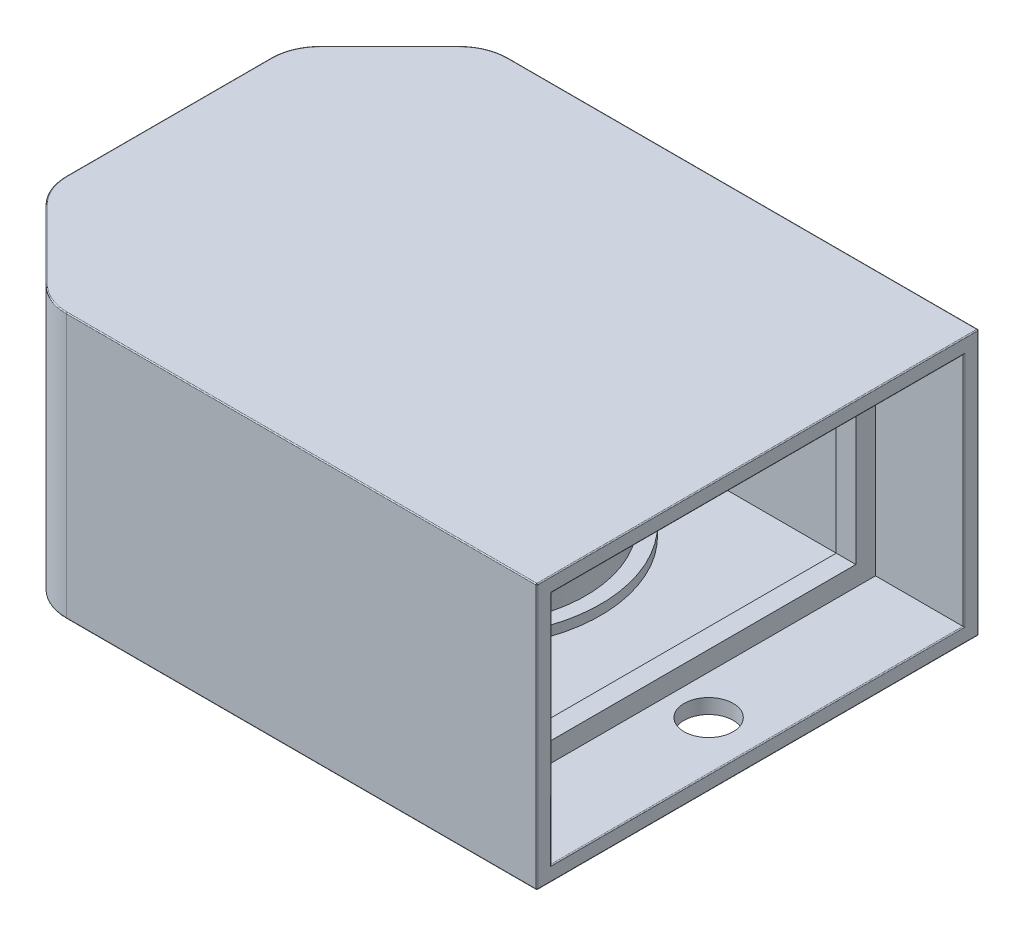
SolidWorks part; units mm, degrees
ref_plane "前视基准面" through (0, 0, 0) normal (0, 0, 1) x (1, 0, 0)
ref_plane "上视基准面" through (0, 0, 0) normal (0, 1, 0) x (1, 0, 0)
ref_plane "右视基准面" through (0, 0, 0) normal (1, 0, 0) x (0, 0, -1)
sketch "草图1" plane through (0, 0, 0) normal (0, 1, 0) x (1, 0, 0)
  line L1 (-30, -22.5) -> (30, -22.5)
  line L2 (-30, -22.5) -> (-30, 22.5)
  line L3 (-30, 22.5) -> (30, 22.5)
  line L4 (30, -22.5) -> (30, 22.5)
  line L5 (-30, -22.5) -> (30, 22.5) construction
  line L6 (-30, 22.5) -> (30, -22.5) construction
  point P0 (0, 0)
  dimension "D1" = 45
  dimension "D2" = 60
extrude "凸台-拉伸1" add sketch "草图1" along normal mid plane 27
chamfer "倒角1" distance 10 angle 45 2 edges at (-30, 0, -22.5) (-30, 0, 22.5)
fillet "圆角1" radius 5 4 edges at (-20, 0, -22.5) (-30, 0, -12.5) (-30, 0, 12.5) (-20, 0, 22.5)
shell "抽壳1" thickness 1.5
fillet "圆角2" radius 0.1 26 edges at (30, 0, -21) (30, 12, 0) (30, 0, 21) (30, -12, 0) (30, 0, 22.5) (30, 0, -22.5) (-29.6194, -13.5, -12.3423) (-30, -13.5, 0) (-29.6194, -13.5, 12.3423) (-25, -13.5, 17.5) (-19.8423, -13.5, 22.1194) (6.0355, -13.5, 22.5) (30, -13.5, 0) (6.0355, -13.5, -22.5) (-19.8423, -13.5, -22.1194) (-25, -13.5, -17.5) (30, 13.5, 0) (6.0355, 13.5, 22.5) (-19.8423, 13.5, 22.1194) (-25, 13.5, 17.5) (-29.6194, 13.5, 12.3423) (-30, 13.5, 0) (-29.6194, 13.5, -12.3423) (-25, 13.5, -17.5) (-19.8423, 13.5, -22.1194) (6.0355, 13.5, -22.5)
sketch "草图3" plane through (0, 0, 0) normal (0, 0, 1) x (1, 0, 0)
  line L0 (0, 13.4) -> (0, -13.4) construction
  line L1 (29.9, 13.4) -> (-17.9289, 13.4) construction
  line L2 (-17.9289, -13.4) -> (29.9, -13.4) construction
  line L3 (0, 12) -> (4, 12)
  line L4 (-17.9289, 12) -> (29.9, 12) construction
  line L5 (4, 12) -> (4, 3.5)
  line L6 (4, 3.5) -> (14, 3.5)
  line L7 (14, 3.5) -> (14, 2.5)
  line L8 (14, 2.5) -> (12.5, 2.5)
  line L9 (12.5, 2.5) -> (12.5, -7.5)
  line L10 (12.5, -7.5) -> (14, -7.5)
  line L11 (14, -7.5) -> (14, -8.5)
  line L12 (14, -8.5) -> (4, -8.5)
  line L13 (4, -8.5) -> (4, -12)
  line L14 (-17.9289, -12) -> (29.9, -12) construction
  line L15 (4, -12) -> (0, -12)
  line L16 (0, -12) -> (0, 12)
  dimension "D1" = 1
  dimension "D2" = 1.5
  dimension "D3" = 25
  dimension "D4" = 3.5
  dimension "D5" = 8
  dimension "D6" = 10
revolve "旋转1" add sketch "草图3" angle 360 about L0
ref_plane "基准面1" through (20, 0, 0) normal (1, 0, 0) x (0, 0, -1)
sketch "草图4" plane through (20, 0, 0) normal (1, 0, 0) x (0, 0, -1)
  line L1 (-21, -12) -> (21, -12)
  line L2 (-21, -12) -> (-21, 12)
  line L3 (-21, 12) -> (21, 12)
  line L4 (21, -12) -> (21, 12)
extrude "拉伸-薄壁1" add sketch "草图4" along normal mid plane 2 thin thin type one direction reverse wall 2
sketch "草图7" plane through (0, -12, 0) normal (0, 1, 0) x (1, 0, 0)
  line L0 (30, 22.4) -> (30, -22.4) construction
  circle A0 centre (25, 0) radius 2.5
  dimension "D1" = 5
  dimension "D2" = 5
extrude "切除-拉伸1" cut sketch "草图7" against normal up to next
